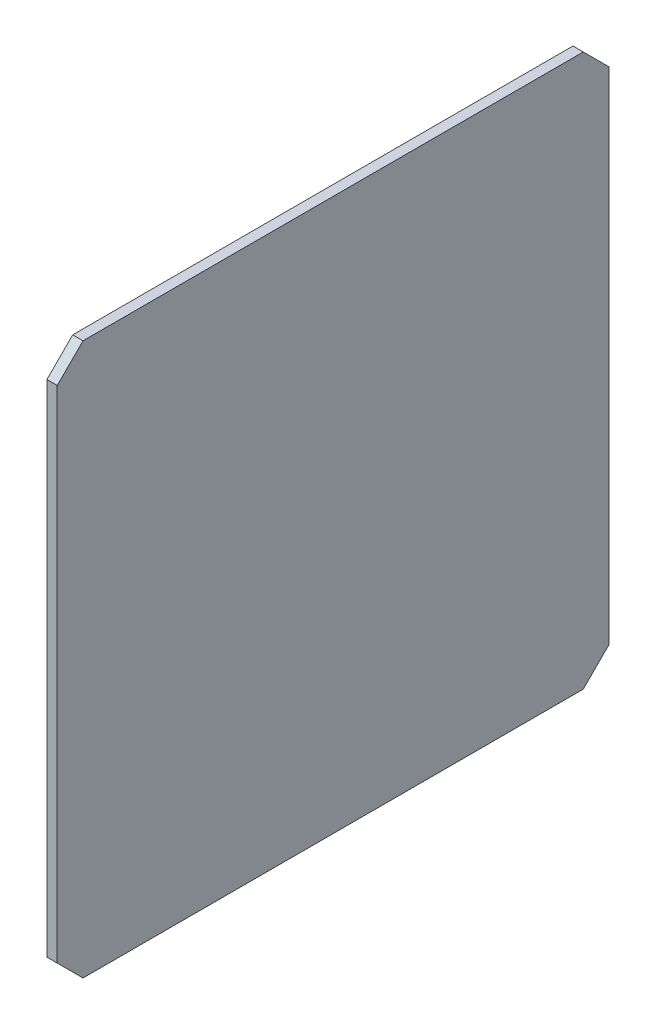
SolidWorks part; units mm, degrees
material "ABS PC"
ref_plane "Front Plane" through (0, 0, 0) normal (0, 0, 1) x (1, 0, 0)
ref_plane "Top Plane" through (0, 0, 0) normal (0, 1, 0) x (1, 0, 0)
ref_plane "Right Plane" through (0, 0, 0) normal (1, 0, 0) x (0, 0, -1)
sketch "Sketch1" plane through (0, 0, 0) normal (1, 0, 0) x (0, 0, -1)
  line L0 (-107, 97) -> (-97, 107)
  line L1 (-97, 107) -> (97, 107)
  line L2 (-107, 97) -> (-107, -97)
  line L3 (-97, -107) -> (97, -107)
  line L4 (107, 97) -> (107, -97)
  line L5 (-107, 107) -> (107, -107) construction
  line L6 (-107, -107) -> (107, 107) construction
  line L7 (97, 107) -> (107, 97)
  line L8 (107, -97) -> (97, -107)
  line L9 (-107, -97) -> (-97, -107)
  point P0 (0, 0)
  dimension "D1" = 214
extrude "Boss-Extrude1" add sketch "Sketch1" along normal blind 4
